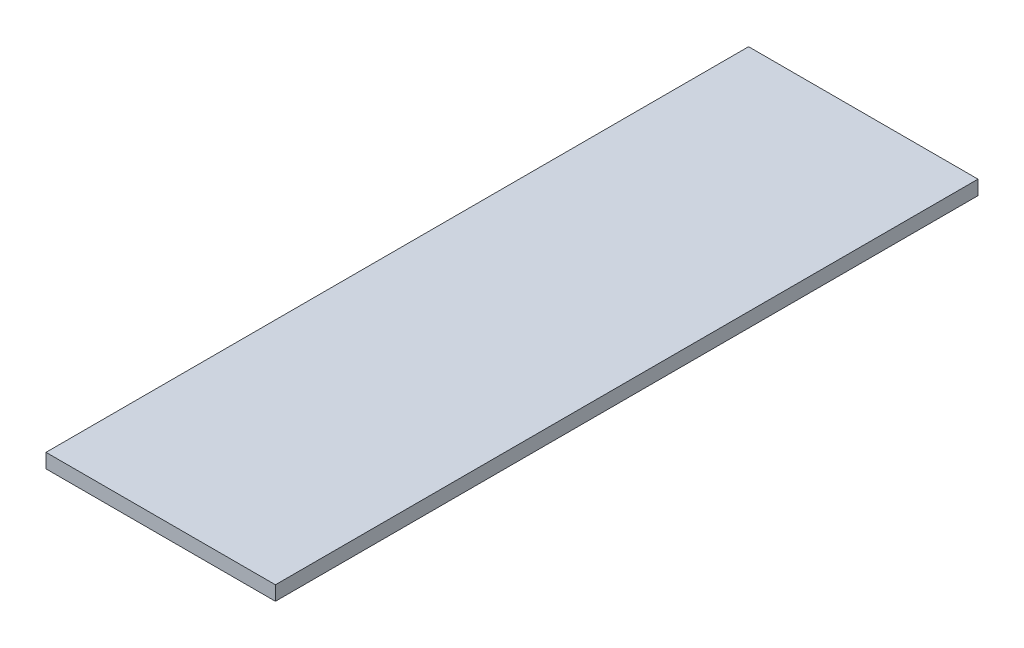
SolidWorks part; units mm, degrees
material "Щебень 40-20"
ref_plane "Спереди" through (0, 0, 0) normal (0, 0, 1) x (1, 0, 0)
ref_plane "Сверху" through (0, 0, 0) normal (0, 1, 0) x (1, 0, 0)
ref_plane "Справа" through (0, 0, 0) normal (1, 0, 0) x (0, 0, -1)
sketch "Эскиз1" plane through (0, 0, 0) normal (0, 1, 0) x (1, 0, 0)
  line L0 (-1050, -6900) -> (1050, -6900) construction
  line L1 (1200, 300) -> (-1200, 300)
  line L2 (1200, 300) -> (1200, -7050)
  line L3 (1200, -7050) -> (-1200, -7050)
  line L4 (-1200, 300) -> (-1200, -7050)
  line L5 (1050, -6900) -> (1050, 150) construction
  line L6 (-1050, 150) -> (-1050, -6900) construction
  line L7 (1050, 150) -> (-1050, 150) construction
  dimension "D1" = 150
  dimension "D2" = 150
  dimension "D3" = 150
  dimension "D4" = 150
extrude "Бобышка-Вытянуть1" add sketch "Эскиз1" against normal blind 150
